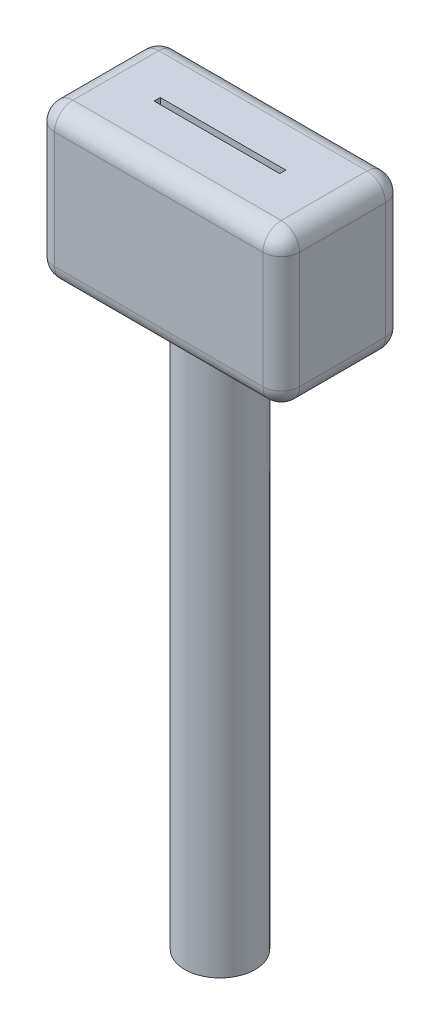
SolidWorks part; units mm, degrees
ref_plane "前视基准面" through (0, 0, 0) normal (0, 0, 1) x (1, 0, 0)
ref_plane "上视基准面" through (0, 0, 0) normal (0, 1, 0) x (1, 0, 0)
ref_plane "右视基准面" through (0, 0, 0) normal (1, 0, 0) x (0, 0, -1)
other "Configuration Table"
sketch "草图1" plane through (0, 0, 0) normal (0, 1, 0) x (1, 0, 0)
  circle A0 centre (0, 0) radius 5.75
  dimension "D1" = 11.5
extrude "凸台-拉伸1" add sketch "草图1" along normal blind 90
sketch "草图2" plane through (0, 90, 0) normal (0, 1, 0) x (1, 0, 0)
  line L1 (-20, -10) -> (20, -10)
  line L2 (-20, -10) -> (-20, 10)
  line L3 (-20, 10) -> (20, 10)
  line L4 (20, -10) -> (20, 10)
  line L5 (-20, -10) -> (20, 10) construction
  line L6 (-20, 10) -> (20, -10) construction
  point P0 (0, 0)
  dimension "D1" = 40
  dimension "D2" = 20
extrude "凸台-拉伸2" add sketch "草图2" along normal blind 25
sketch "草图3" plane through (0, 115, 0) normal (0, 1, 0) x (1, 0, 0)
  line L1 (-10.25, -0.5) -> (10.25, -0.5)
  line L2 (-10.25, -0.5) -> (-10.25, 0.5)
  line L3 (-10.25, 0.5) -> (10.25, 0.5)
  line L4 (10.25, -0.5) -> (10.25, 0.5)
  line L5 (-10.25, -0.5) -> (10.25, 0.5) construction
  line L6 (-10.25, 0.5) -> (10.25, -0.5) construction
  point P0 (0, 0)
  dimension "D1" = 20.5
  dimension "D2" = 1
extrude "切除-拉伸1" cut sketch "草图3" against normal blind 20
fillet "圆角1" radius 3 12 edges at (20, 102.5, -10) (0, 115, -10) (-20, 102.5, -10) (0, 90, -10) (-20, 102.5, 10) (0, 115, 10) (20, 102.5, 10) (0, 90, 10) (-20, 115, 0) (-20, 90, 0) (20, 115, 0) (20, 90, 0)
